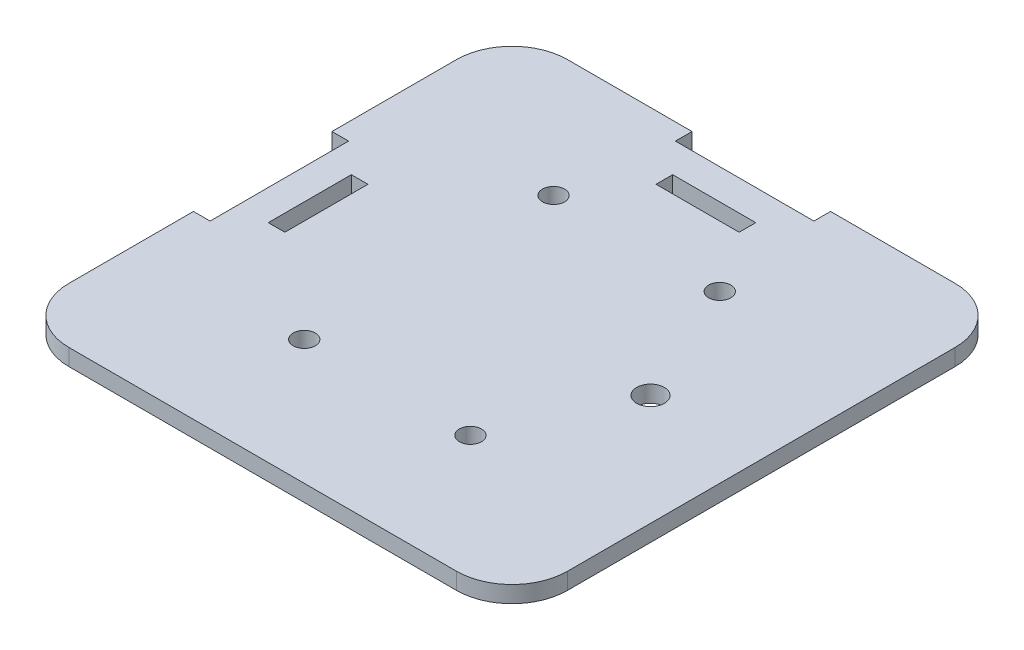
SolidWorks part; units mm, degrees
ref_plane "Front Plane" through (0, 0, 0) normal (0, 0, 1) x (1, 0, 0)
ref_plane "Top Plane" through (0, 0, 0) normal (0, 1, 0) x (1, 0, 0)
ref_plane "Right Plane" through (0, 0, 0) normal (1, 0, 0) x (0, 0, -1)
sketch "Sketch1" plane through (0, 0, 0) normal (0, 1, 0) x (1, 0, 0)
  line L1 (35, -45) -> (-35, -45)
  line L2 (45, -35) -> (45, 35)
  line L3 (35, 45) -> (-35, 45)
  line L4 (-45, -35) -> (-45, 35)
  line L5 (45, -45) -> (-45, 45) construction
  line L6 (45, 45) -> (-45, -45) construction
  line L7 (-45, 12.5) -> (-42, 12.5)
  line L8 (-45, 12.5) -> (-45, -12.5)
  line L9 (-45, -12.5) -> (-42, -12.5)
  line L10 (-42, 12.5) -> (-42, -12.5)
  line L11 (-12.5, 45) -> (12.5, 45)
  line L12 (-12.5, 45) -> (-12.5, 42)
  line L13 (-12.5, 42) -> (12.5, 42)
  line L14 (12.5, 45) -> (12.5, 42)
  arc A0 (-45, -35) -> (-35, -45) centre (-35, -35) ccw
  arc A1 (35, -45) -> (45, -35) centre (35, -35) ccw
  arc A2 (45, 35) -> (35, 45) centre (35, 35) ccw
  arc A3 (-45, 35) -> (-35, 45) centre (-35, 35) cw
  point P0 (0, 0)
  point P22 (-42, 0)
  point P23 (-45, 0)
  point P28 (0, 42)
  point P29 (0, 45)
  dimension "D1" = 10
  dimension "D2" = 3
  dimension "D3" = 25
  dimension "D4" = 0
  dimension "D5" = 3
  dimension "D6" = 25
  dimension "D7" = 0
  dimension "D8" = 90
  dimension "D9" = 90
extrude "Boss-Extrude1" add sketch "Sketch1" along normal blind 3 contours A3 L4 L7 L10 L9 A0 L1 A1 L2 A2 L3 L14 L13 L12
sketch "Sketch2" plane through (0, 3, 0) normal (0, 1, 0) x (1, 0, 0)
  line L0 (0, -1.65) -> (0, 1.65) construction
  line L1 (-1.65, 0) -> (1.65, 0) construction
  circle A0 centre (-15, 22.5) radius 2
  circle A1 centre (15, 22.5) radius 2
  circle A2 centre (15, -22.5) radius 2
  circle A3 centre (-15, -22.5) radius 2
  dimension "D1" = 15
  dimension "D2" = 22.5
extrude "Cut-Extrude1" cut sketch "Sketch2" against normal blind 3
sketch "Sketch3" plane through (0, 3, 0) normal (0, 1, 0) x (1, 0, 0)
  line L1 (7.5, 33.5) -> (-7.5, 33.5)
  line L2 (7.5, 33.5) -> (7.5, 36.5)
  line L3 (7.5, 36.5) -> (-7.5, 36.5)
  line L4 (-7.5, 33.5) -> (-7.5, 36.5)
  line L5 (7.5, 33.5) -> (-7.5, 36.5) construction
  line L6 (7.5, 36.5) -> (-7.5, 33.5) construction
  line L7 (-33.5, -7.5) -> (-36.5, -7.5)
  line L8 (-33.5, -7.5) -> (-33.5, 7.5)
  line L9 (-33.5, 7.5) -> (-36.5, 7.5)
  line L10 (-36.5, -7.5) -> (-36.5, 7.5)
  line L11 (-33.5, -7.5) -> (-36.5, 7.5) construction
  line L12 (-33.5, 7.5) -> (-36.5, -7.5) construction
  point P0 (0, 35)
  point P5 (-35, 0)
  dimension "D1" = 15
  dimension "D2" = 3
  dimension "D3" = 35
  dimension "D4" = 0
  dimension "D5" = 3
  dimension "D6" = 15
  dimension "D7" = 0
  dimension "D8" = 35
extrude "Cut-Extrude2" cut sketch "Sketch3" against normal blind 10
sketch "Sketch4" plane through (0, 3, 0) normal (0, 1, 0) x (1, 0, 0)
  circle A0 centre (25, 0) radius 2.5
  dimension "D1" = 25
extrude "Cut-Extrude3" cut sketch "Sketch4" against normal blind 14
